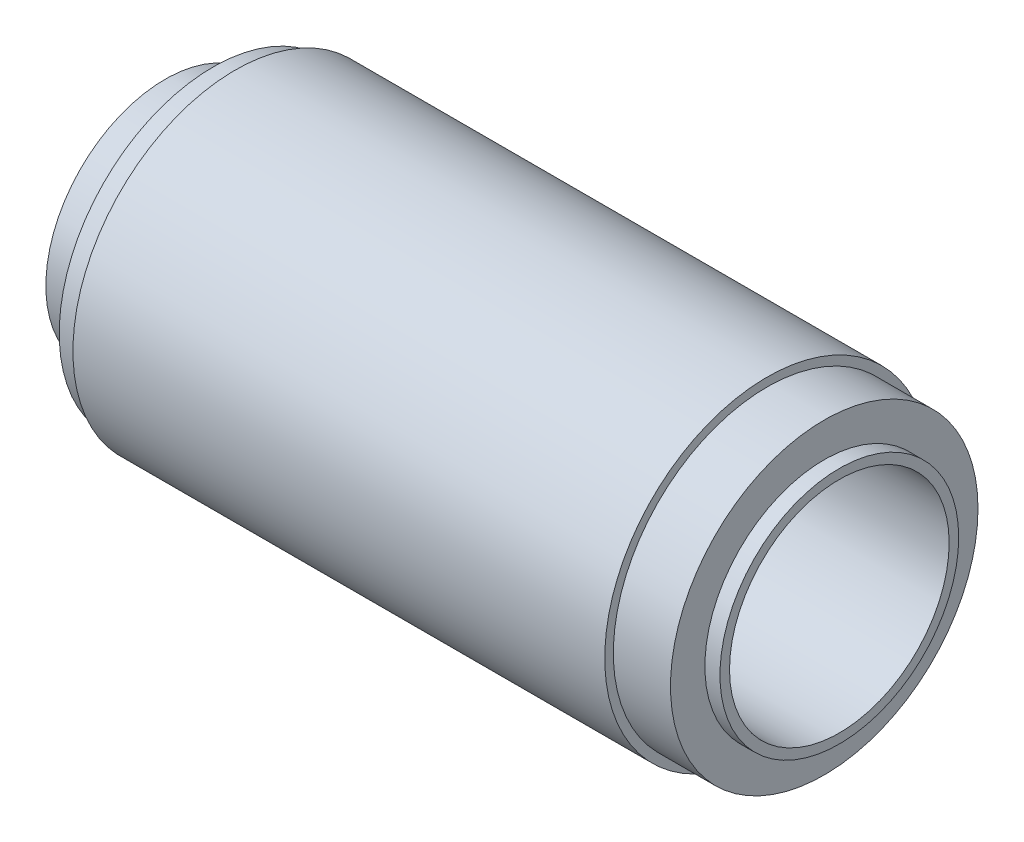
SolidWorks part; units mm, degrees
ref_plane "Front Plane" through (0, 0, 0) normal (0, 0, 1) x (1, 0, 0)
ref_plane "Top Plane" through (0, 0, 0) normal (0, 1, 0) x (1, 0, 0)
ref_plane "Right Plane" through (0, 0, 0) normal (1, 0, 0) x (0, 0, -1)
sketch "Sketch1" plane through (0, 0, 0) normal (0, 1, 0) x (1, 0, 0)
  line L0 (0, 0) -> (-126.7378, 0) construction
  line L1 (-30.6, -11.5) -> (-30.6, -12.5)
  line L2 (-30.6, -12.5) -> (-32.18, -12.5)
  line L3 (-32.18, -12.5) -> (-32.18, -16.1)
  line L4 (-32.18, -16.1) -> (-38.1654, -16.1)
  line L5 (-38.1654, -16.1) -> (-38.1654, -17)
  line L6 (-38.1654, -17) -> (-93.8537, -17)
  line L7 (-93.8537, -17) -> (-93.8537, -16.1)
  line L8 (-93.8537, -16.1) -> (-96.19, -16.1)
  line L9 (-96.19, -16.1) -> (-96.19, -12.5)
  line L10 (-96.19, -12.5) -> (-101.19, -12.5)
  line L11 (-101.19, -12.5) -> (-101.19, -11.5)
  line L12 (-101.19, -11.5) -> (-30.6, -11.5)
  dimension "D1" = 30.6
  dimension "D2" = 1.58
  dimension "D3" = 96.19
  dimension "D4" = 34
  dimension "D5" = 32.2
  dimension "D6" = 25
  dimension "D7" = 23
  dimension "D8" = 5
revolve "Revolve1" add sketch "Sketch1" angle 360 about L0
